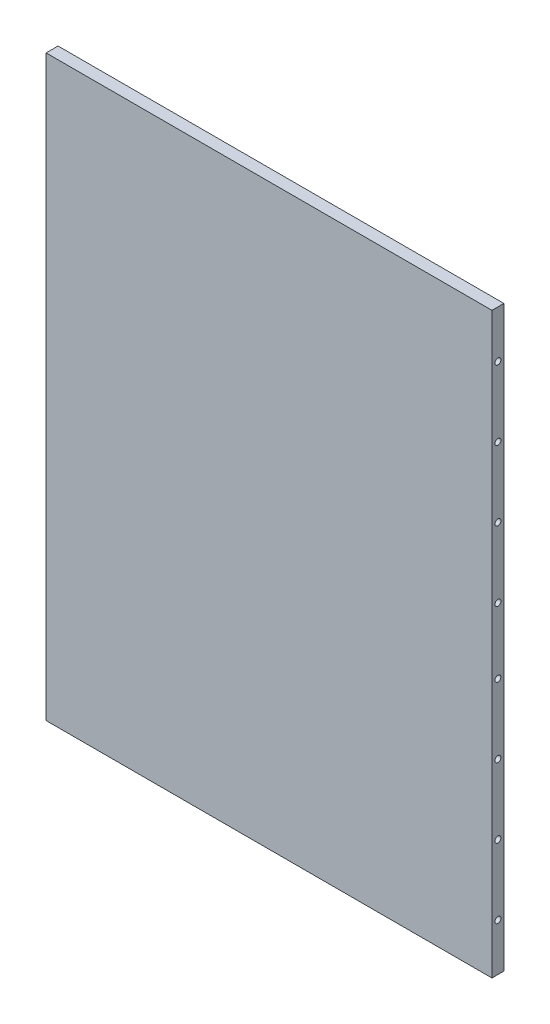
SolidWorks part; units mm, degrees
ref_plane "Alzado" through (0, 0, 0) normal (0, 0, 1) x (1, 0, 0)
ref_plane "Planta" through (0, 0, 0) normal (0, 1, 0) x (1, 0, 0)
ref_plane "Vista lateral" through (0, 0, 0) normal (1, 0, 0) x (0, 0, -1)
sketch "Croquis1" plane through (0, 0, 0) normal (0, 0, 1) x (1, 0, 0)
  line L1 (224, 290.5) -> (-224, 290.5)
  line L2 (224, 290.5) -> (224, -290.5)
  line L3 (224, -290.5) -> (-224, -290.5)
  line L4 (-224, 290.5) -> (-224, -290.5)
  dimension "D1" = 448
  dimension "D2" = 581
  dimension "D3" = 224
  dimension "D4" = 290.5
extrude "Saliente-Extruir2" add sketch "Croquis1" along normal mid plane 12
sketch "Croquis3" plane through (0, 0, 0) normal (1, 0, 0) x (0, 0, -1)
  line L0 (-6, 290.5) -> (6, 290.5) construction
  line L1 (-37.0183, 0) -> (52.3914, 0) construction
  circle A0 centre (0, 243) radius 3
  circle A1 centre (0, 173) radius 3
  circle A2 centre (0, 103) radius 3
  circle A3 centre (0, 33) radius 3
  circle A4 centre (0, -33) radius 3
  circle A5 centre (0, -103) radius 3
  circle A6 centre (0, -173) radius 3
  circle A7 centre (0, -243) radius 3
  dimension "D1" = 47.5
  dimension "D2" = 4
extrude "Cortar-Extruir2" cut sketch "Croquis3" against normal blind 27 from offset 225
mirror "Simetría1" about plane through (0, 0, 0) normal (1, 0, 0) of "Cortar-Extruir2"
sketch "Croquis4" plane through (0, 0, 0) normal (0, 1, 0) x (1, 0, 0)
  line L0 (-224, -6) -> (-224, 6) construction
  line L1 (0, 6) -> (0, -6) construction
  line L2 (224, 6) -> (-224, 6) construction
  line L3 (224, -6) -> (-224, -6) construction
  circle A0 centre (-176.5, 0) radius 3
  circle A1 centre (-106.5, 0) radius 3
  circle A2 centre (-36.5, 0) radius 3
  circle A3 centre (36.5, 0) radius 3
  circle A4 centre (106.5, 0) radius 3
  circle A5 centre (176.5, 0) radius 3
  dimension "D1" = 47.5
  dimension "D2" = 3
extrude "Cortar-Extruir3" cut sketch "Croquis4" against normal blind 27 from offset 290
mirror "Simetría2" about plane through (0, 0, 0) normal (0, 1, 0) of "Cortar-Extruir3"
